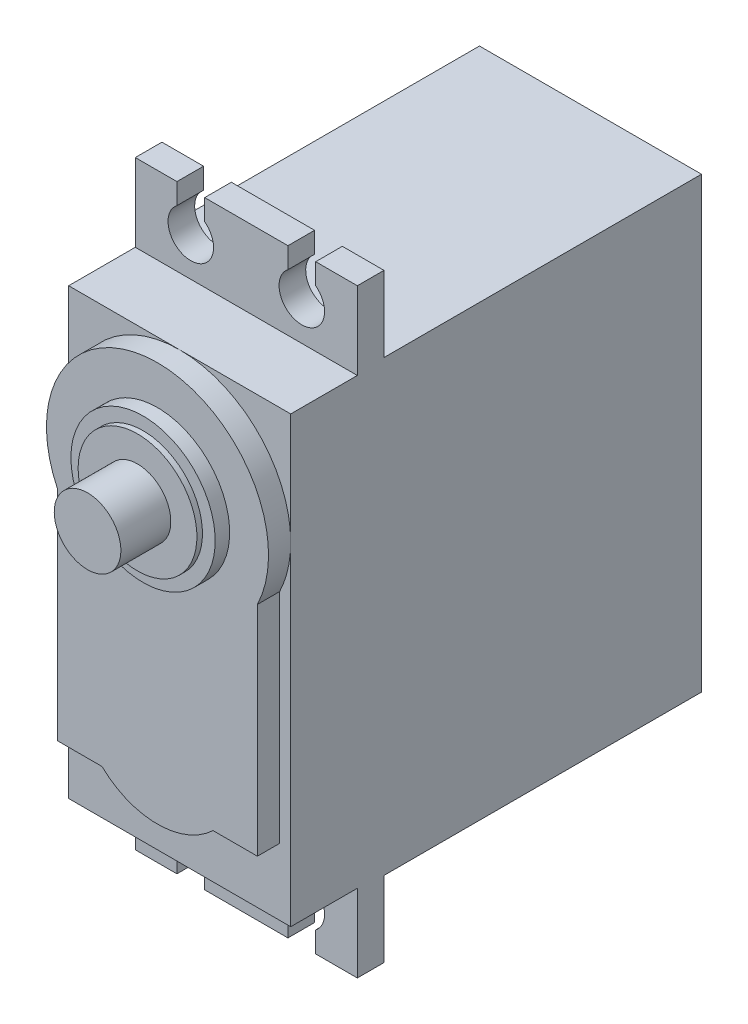
SolidWorks part; units mm, degrees
ref_plane "Plan de face" through (0, 0, 0) normal (0, 0, 1) x (1, 0, 0)
ref_plane "Plan de dessus" through (0, 0, 0) normal (0, 1, 0) x (1, 0, 0)
ref_plane "Plan de droite" through (0, 0, 0) normal (1, 0, 0) x (0, 0, -1)
ref_plane "Plan1" through (10, 0, 0) normal (1, 0, 0) x (0, 0, -1)
sketch "Esquisse1" plane through (10, 0, 0) normal (1, 0, 0) x (0, 0, -1)
  line L0 (0, 27) -> (-37, 27)
  line L1 (-37, 27) -> (-37, -27)
  line L2 (-37, -27) -> (0, -27)
  line L3 (0, -27) -> (0, 27)
extrude "Boss.-Extru.1" add sketch "Esquisse1" against normal blind 20
sketch "Esquisse2" plane through (0, 0, 37) normal (0, 0, 1) x (1, 0, 0)
  line L0 (-9, -14) -> (-9, 5.6411)
  line L1 (9, 5.6411) -> (9, -14)
  line L2 (9, -14) -> (-9, -14)
  arc A0 (-9, 5.6411) -> (9, 5.6411) centre (0, 10) cw
extrude "Boss.-Extru.2" add sketch "Esquisse2" along normal blind 2
sketch "Esquisse3" plane through (10, 0, 0) normal (1, 0, 0) x (0, 0, -1)
  line L0 (-37, 27) -> (-37, 20)
  line L1 (-37, 20) -> (-31, 20)
  line L2 (-31, 20) -> (-31, 27)
  line L3 (-31, 27) -> (-37, 27)
extrude "Enlèv. mat.-Extru.1" cut sketch "Esquisse3" against normal through all
sketch "Esquisse4" plane through (-10, 0, 0) normal (-1, 0, 0) x (0, 0, 1)
  line L0 (31, -20) -> (31, -27)
  line L1 (31, -27) -> (37, -27)
  line L2 (37, -27) -> (37, -20)
  line L3 (37, -20) -> (31, -20)
extrude "Enlèv. mat.-Extru.2" cut sketch "Esquisse4" against normal through all
sketch "Esquisse5" plane through (0, 0, 37) normal (0, 0, 1) x (1, 0, 0)
  line L0 (-5, -14) -> (5, -14)
  arc A0 (5, -14) -> (-5, -14) centre (0, -8.75) cw
extrude "Boss.-Extru.3" add sketch "Esquisse5" along normal blind 2
sketch "Esquisse6" plane through (-10, 0, 0) normal (-1, 0, 0) x (0, 0, 1)
  line L0 (0, -27) -> (28.6, -27)
  line L1 (28.6, -27) -> (28.6, -20.2)
  line L2 (28.6, -20.2) -> (0, -20.2)
  line L3 (0, -20.2) -> (0, -27)
extrude "Enlèv. mat.-Extru.3" cut sketch "Esquisse6" against normal through all
sketch "Esquisse7" plane through (0, 0, 28.6) normal (0, 0, -1) x (-1, 0, 0)
  line L0 (3.75, -27) -> (6.25, -27)
  line L1 (6.25, -27) -> (6.25, -25.1248)
  line L2 (3.75, -25.1248) -> (3.75, -27)
  arc A0 (6.25, -25.1248) -> (3.75, -25.1248) centre (5, -23.5) cw
extrude "Enlèv. mat.-Extru.4" cut sketch "Esquisse7" against normal through all
sketch "Esquisse8" plane through (0, 0, 28.6) normal (0, 0, -1) x (-1, 0, 0)
  line L0 (-6.25, -27) -> (-3.75, -27)
  line L1 (-3.75, -27) -> (-3.75, -25.1248)
  line L2 (-6.25, -25.1248) -> (-6.25, -27)
  arc A0 (-3.75, -25.1248) -> (-6.25, -25.1248) centre (-5, -23.5) cw
extrude "Enlèv. mat.-Extru.5" cut sketch "Esquisse8" against normal through all
sketch "Esquisse9" plane through (-10, 0, 0) normal (-1, 0, 0) x (0, 0, 1)
  line L0 (0, 27) -> (0, 20.2)
  line L1 (0, 20.2) -> (28.6, 20.2)
  line L2 (28.6, 20.2) -> (28.6, 27)
  line L3 (28.6, 27) -> (0, 27)
extrude "Enlèv. mat.-Extru.6" cut sketch "Esquisse9" against normal through all
sketch "Esquisse10" plane through (0, 0, 31) normal (0, 0, 1) x (1, 0, 0)
  line L0 (-3.75, 27) -> (-6.25, 27)
  line L1 (-6.25, 27) -> (-6.25, 25.1248)
  line L2 (-3.75, 25.1248) -> (-3.75, 27)
  arc A0 (-6.25, 25.1248) -> (-3.75, 25.1248) centre (-5, 23.5) cw
extrude "Enlèv. mat.-Extru.7" cut sketch "Esquisse10" against normal through all
sketch "Esquisse11" plane through (0, 0, 31) normal (0, 0, 1) x (1, 0, 0)
  line L0 (6.25, 27) -> (3.75, 27)
  line L1 (3.75, 27) -> (3.75, 25.1248)
  line L2 (6.25, 25.1248) -> (6.25, 27)
  arc A0 (3.75, 25.1248) -> (6.25, 25.1248) centre (5, 23.5) cw
extrude "Enlèv. mat.-Extru.8" cut sketch "Esquisse11" against normal through all
ref_plane "Plan2" through (0, 23.5, 0) normal (0, 1, 0) x (1, 0, 0)
sketch "Esquisse12" plane through (0, 23.5, 0) normal (0, 1, 0) x (1, 0, 0)
  line L0 (7.05, -28.6) -> (5, -28.6)
  line L1 (5, -28.6) -> (5, -31)
  line L2 (5, -31) -> (7.05, -31)
  line L3 (7.05, -31) -> (7.05, -28.6)
  line L4 (5, -28.6) -> (5, -31) construction
revolve "Enlèvement de matière-Révolution1" cut sketch "Esquisse12" angle 360 about L4
ref_plane "Plan3" through (0, 23.5, 0) normal (0, -1, 0) x (1, 0, 0)
sketch "Esquisse13" plane through (0, 23.5, 0) normal (0, -1, 0) x (1, 0, 0)
  line L0 (-2.95, 31) -> (-5, 31)
  line L1 (-5, 31) -> (-5, 28.6)
  line L2 (-5, 28.6) -> (-2.95, 28.6)
  line L3 (-2.95, 28.6) -> (-2.95, 31)
  line L4 (-5, 31) -> (-5, 28.6) construction
revolve "Enlèvement de matière-Révolution2" cut sketch "Esquisse13" angle 360 about L4
ref_plane "Plan4" through (0, -23.5, 0) normal (0, 1, 0) x (1, 0, 0)
sketch "Esquisse14" plane through (0, -23.5, 0) normal (0, 1, 0) x (1, 0, 0)
  line L0 (-2.95, -28.6) -> (-5, -28.6)
  line L1 (-5, -28.6) -> (-5, -31)
  line L2 (-5, -31) -> (-2.95, -31)
  line L3 (-2.95, -31) -> (-2.95, -28.6)
  line L4 (-5, -28.6) -> (-5, -31) construction
revolve "Enlèvement de matière-Révolution3" cut sketch "Esquisse14" angle 360 about L4
ref_plane "Plan5" through (0, -23.5, 0) normal (0, -1, 0) x (1, 0, 0)
sketch "Esquisse15" plane through (0, -23.5, 0) normal (0, -1, 0) x (1, 0, 0)
  line L0 (7.05, 31) -> (5, 31)
  line L1 (5, 31) -> (5, 28.6)
  line L2 (5, 28.6) -> (7.05, 28.6)
  line L3 (7.05, 28.6) -> (7.05, 31)
  line L4 (5, 31) -> (5, 28.6) construction
revolve "Enlèvement de matière-Révolution4" cut sketch "Esquisse15" angle 360 about L4
ref_plane "Plan6" through (0, 10, 0) normal (0, -1, 0) x (1, 0, 0)
sketch "Esquisse16" plane through (0, 10, 0) normal (0, -1, 0) x (1, 0, 0)
  line L0 (3, 45.3) -> (0, 45.3)
  line L1 (0, 45.3) -> (0, 39)
  line L2 (0, 39) -> (6.5, 39)
  line L3 (6.5, 39) -> (6.5, 40.3)
  line L4 (6.5, 40.3) -> (5.35, 40.3)
  line L5 (5.35, 40.3) -> (5.35, 40.8)
  line L6 (5.35, 40.8) -> (3, 40.8)
  line L7 (3, 40.8) -> (3, 45.3)
  line L8 (0, 45.3) -> (0, 39) construction
revolve "Révolution1" add sketch "Esquisse16" angle 360 about L8
